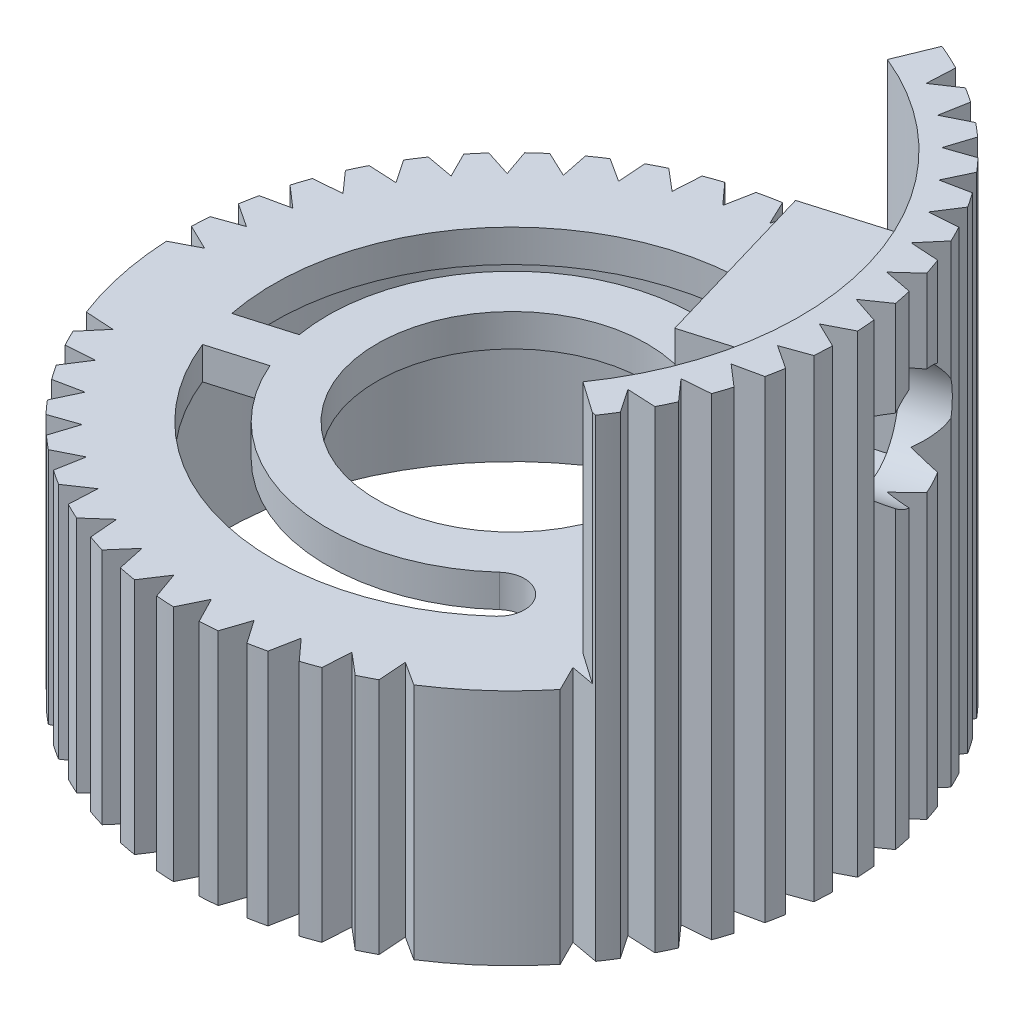
SolidWorks part; units mm, degrees
material "VeroWhite Plus"
ref_plane "Front Plane" through (0, 0, 0) normal (0, 0, 1) x (1, 0, 0)
ref_plane "Top Plane" through (0, 0, 0) normal (0, 1, 0) x (1, 0, 0)
ref_plane "Right Plane" through (0, 0, 0) normal (1, 0, 0) x (0, 0, -1)
sketch "Sketch1" plane through (0, 0, 0) normal (0, 1, 0) x (1, 0, 0)
  line L0 (9.9132, 31.394) -> (7.112, 32.1446) construction
  line L1 (11.113, 31.0725) -> (5.9121, 32.4661) construction
  line L2 (8.5126, 31.7693) -> (0, 0) construction
  line L3 (0, 0) -> (-6.2397, 29.8549) construction
  line L4 (0, 0) -> (-5.194, 30.0545) construction
  line L5 (0, 0) -> (-4.3196, 30.1926) construction
  line L6 (-4.9343, 30.0982) -> (-4.1426, 28.9552) construction
  line L7 (-4.1426, 28.9552) -> (-3.7032, 30.2744) construction
  line L8 (5.9121, 32.4661) -> (4.002, 25.3375) construction
  line L9 (11.113, 31.0725) -> (9.4356, 24.8123) construction
  line L10 (-32.4661, -5.9121) -> (-31.0725, -11.113) construction
  line L11 (-32.1446, -7.112) -> (-31.394, -9.9131) construction
  line L12 (22.2314, -24.282) -> (24.282, -22.2314) construction
  line L13 (-31.7693, -8.5126) -> (0, 0) construction
  line L14 (0, 0) -> (23.2567, -23.2567) construction
  line L15 (25.1604, -21.3531) -> (18.9649, -15.1575) construction
  line L16 (21.3531, -25.1604) -> (14.6891, -18.4964) construction
  line L17 (-32.4661, -5.9121) -> (-24.142, -3.6817) construction
  line L18 (-31.0725, -11.113) -> (-21.737, -8.6116) construction
  line L19 (-0.9635, 30.4848) -> (-0.3278, 29.2482) construction
  line L20 (-0.3278, 29.2482) -> (0.2801, 30.4987) construction
  line L21 (3.0238, 30.3497) -> (3.4927, 29.0407) construction
  line L22 (3.4927, 29.0407) -> (4.2586, 30.2012) construction
  line L23 (14.408, 26.8823) -> (14.3402, 25.4935) construction
  line L24 (14.3402, 25.4935) -> (15.4919, 26.2726) construction
  line L25 (17.7936, 24.7717) -> (17.5451, 23.4037) construction
  line L26 (17.5451, 23.4037) -> (18.7887, 24.0257) construction
  line L27 (20.8747, 22.2373) -> (20.4498, 20.9133) construction
  line L28 (20.4498, 20.9133) -> (21.7639, 21.3678) construction
  line L29 (23.5987, 19.3223) -> (23.0046, 18.0652) construction
  line L30 (23.0046, 18.0652) -> (24.3668, 18.3442) construction
  line L31 (25.9189, 16.0768) -> (25.1658, 14.9079) construction
  line L32 (25.1658, 14.9079) -> (26.5527, 15.0068) construction
  line L33 (27.7956, 12.5562) -> (26.8964, 11.4956) construction
  line L34 (26.8964, 11.4956) -> (28.2843, 11.4126) construction
  line L35 (29.1967, 8.8207) -> (28.1667, 7.8866) construction
  line L36 (28.1667, 7.8866) -> (29.532, 7.6231) construction
  line L37 (30.0982, 4.9343) -> (28.9552, 4.1426) construction
  line L38 (28.9552, 4.1426) -> (30.2744, 3.7032) construction
  line L39 (30.4848, 0.9635) -> (29.2482, 0.3278) construction
  line L40 (29.2482, 0.3278) -> (30.4987, -0.2801) construction
  line L41 (30.3497, -3.0238) -> (29.0407, -3.4927) construction
  line L42 (29.0407, -3.4927) -> (30.2012, -4.2586) construction
  line L43 (29.6954, -6.9594) -> (28.3364, -7.2534) construction
  line L44 (28.3364, -7.2534) -> (29.387, -8.1642) construction
  line L45 (28.533, -10.7759) -> (27.1472, -10.89) construction
  line L46 (27.1472, -10.89) -> (28.07, -11.9301) construction
  line L47 (26.8823, -14.408) -> (25.4935, -14.3402) construction
  line L48 (25.4935, -14.3402) -> (26.2726, -15.4919) construction
  line L49 (24.7717, -17.7936) -> (23.4037, -17.5451) construction
  line L50 (23.4037, -17.5451) -> (24.0257, -18.7887) construction
  line L51 (16.0768, -25.9188) -> (14.9079, -25.1658) construction
  line L52 (14.9079, -25.1658) -> (15.0068, -26.5527) construction
  line L53 (12.5562, -27.7955) -> (11.4956, -26.8963) construction
  line L54 (11.4956, -26.8963) -> (11.4126, -28.2843) construction
  line L55 (8.8207, -29.1967) -> (7.8866, -28.1667) construction
  line L56 (7.8866, -28.1667) -> (7.6231, -29.532) construction
  line L57 (4.9343, -30.0982) -> (4.1426, -28.9552) construction
  line L58 (4.1426, -28.9552) -> (3.7032, -30.2743) construction
  line L59 (0.9635, -30.4848) -> (0.3278, -29.2482) construction
  line L60 (0.3278, -29.2482) -> (-0.2801, -30.4987) construction
  line L61 (-3.0238, -30.3497) -> (-3.4927, -29.0407) construction
  line L62 (-3.4927, -29.0407) -> (-4.2586, -30.2012) construction
  line L63 (-6.9594, -29.6954) -> (-7.2534, -28.3364) construction
  line L64 (-7.2534, -28.3364) -> (-8.1642, -29.387) construction
  line L65 (-10.7759, -28.533) -> (-10.89, -27.1472) construction
  line L66 (-10.89, -27.1472) -> (-11.9301, -28.0699) construction
  line L67 (-14.408, -26.8823) -> (-14.3402, -25.4935) construction
  line L68 (-14.3402, -25.4935) -> (-15.4919, -26.2726) construction
  line L69 (-17.7936, -24.7717) -> (-17.5451, -23.4037) construction
  line L70 (-17.5451, -23.4037) -> (-18.7886, -24.0257) construction
  line L71 (-20.8747, -22.2373) -> (-20.4498, -20.9133) construction
  line L72 (-20.4498, -20.9133) -> (-21.7639, -21.3678) construction
  line L73 (-23.5987, -19.3223) -> (-23.0046, -18.0652) construction
  line L74 (-23.0046, -18.0652) -> (-24.3668, -18.3442) construction
  line L75 (-25.9188, -16.0768) -> (-25.1658, -14.9079) construction
  line L76 (-25.1658, -14.9079) -> (-26.5527, -15.0068) construction
  line L77 (-27.7955, -12.5562) -> (-26.8963, -11.4956) construction
  line L78 (-26.8963, -11.4956) -> (-28.2843, -11.4126) construction
  line L79 (-30.4848, -0.9635) -> (-29.2482, -0.3278) construction
  line L80 (-29.2482, -0.3278) -> (-30.4987, 0.2801) construction
  line L81 (-30.3497, 3.0238) -> (-29.0407, 3.4927) construction
  line L82 (-29.0407, 3.4927) -> (-30.2012, 4.2586) construction
  line L83 (-29.6954, 6.9594) -> (-28.3364, 7.2534) construction
  line L84 (-28.3364, 7.2534) -> (-29.387, 8.1642) construction
  line L85 (-28.533, 10.7759) -> (-27.1472, 10.89) construction
  line L86 (-27.1472, 10.89) -> (-28.0699, 11.9301) construction
  line L87 (-26.8823, 14.408) -> (-25.4935, 14.3402) construction
  line L88 (-25.4935, 14.3402) -> (-26.2726, 15.4919) construction
  line L89 (-24.7717, 17.7936) -> (-23.4037, 17.5451) construction
  line L90 (-23.4037, 17.5451) -> (-24.0257, 18.7887) construction
  line L91 (-22.2373, 20.8747) -> (-20.9133, 20.4498) construction
  line L92 (-20.9133, 20.4498) -> (-21.3678, 21.7639) construction
  line L93 (-19.3223, 23.5987) -> (-18.0652, 23.0046) construction
  line L94 (-18.0652, 23.0046) -> (-18.3442, 24.3668) construction
  line L95 (-16.0768, 25.9189) -> (-14.9079, 25.1658) construction
  line L96 (-14.9079, 25.1658) -> (-15.0068, 26.5527) construction
  line L97 (-12.5562, 27.7956) -> (-11.4956, 26.8964) construction
  line L98 (-11.4956, 26.8964) -> (-11.4126, 28.2843) construction
  line L99 (-8.8207, 29.1967) -> (-7.8866, 28.1667) construction
  line L100 (-7.8866, 28.1667) -> (-7.6231, 29.532) construction
  line L101 (-3.9843, 27.8484) -> (-3.1555, 30.3363)
  line L102 (-1.5142, 30.4624) -> (-0.3152, 28.1302)
  line L103 (-0.3152, 28.1302) -> (0.8312, 30.4887)
  line L104 (2.4749, 30.3994) -> (3.3592, 27.9307)
  line L105 (3.3592, 27.9307) -> (4.8036, 30.1194)
  line L106 (13.9199, 27.1383) -> (13.7921, 24.5191)
  line L107 (13.7921, 24.5191) -> (15.9641, 25.9884)
  line L108 (17.3431, 25.0892) -> (16.8745, 22.5091)
  line L109 (16.8745, 22.5091) -> (19.2197, 23.6823)
  line L110 (20.4695, 22.6109) -> (19.6682, 20.114)
  line L111 (19.6682, 20.114) -> (22.1465, 20.971)
  line L112 (23.2457, 19.7456) -> (22.1253, 17.3747)
  line L113 (22.1253, 17.3747) -> (24.6943, 17.9009)
  line L114 (25.6241, 16.5425) -> (24.2039, 14.3381)
  line L115 (24.2039, 14.3381) -> (26.8195, 14.5245)
  line L116 (27.5641, 13.0564) -> (25.8683, 11.0562)
  line L117 (25.8683, 11.0562) -> (28.4859, 10.8996)
  line L118 (29.0325, 9.3468) -> (27.0901, 7.5851)
  line L119 (27.0901, 7.5851) -> (29.6649, 7.0882)
  line L120 (30.0041, 5.4774) -> (27.8484, 3.9843)
  line L121 (27.8484, 3.9843) -> (30.3363, 3.1555)
  line L122 (30.4624, 1.5142) -> (28.1302, 0.3152)
  line L123 (28.1302, 0.3152) -> (30.4887, -0.8312)
  line L124 (30.3994, -2.4749) -> (27.9307, -3.3592)
  line L125 (27.9307, -3.3592) -> (30.1194, -4.8036)
  line L126 (29.8163, -6.4217) -> (27.2533, -6.9761)
  line L127 (27.2533, -6.9761) -> (29.2347, -8.6939)
  line L128 (28.723, -10.2585) -> (26.1096, -10.4737)
  line L129 (26.1096, -10.4737) -> (27.8498, -12.4354)
  line L130 (27.1383, -13.9199) -> (24.5191, -13.7921)
  line L131 (24.5191, -13.7921) -> (25.9884, -15.9641)
  line L132 (25.0892, -17.343) -> (22.5091, -16.8745)
  line L133 (22.5091, -16.8745) -> (23.6823, -19.2197)
  line L134 (16.5425, -25.6241) -> (14.3381, -24.2038)
  line L135 (14.3381, -24.2038) -> (14.5245, -26.8195)
  line L136 (13.0564, -27.5641) -> (11.0562, -25.8683)
  line L137 (11.0562, -25.8683) -> (10.8996, -28.4859)
  line L138 (9.3468, -29.0325) -> (7.5851, -27.0901)
  line L139 (7.5851, -27.0901) -> (7.0882, -29.6649)
  line L140 (5.4774, -30.0041) -> (3.9843, -27.8484)
  line L141 (3.9843, -27.8484) -> (3.1555, -30.3363)
  line L142 (1.5142, -30.4624) -> (0.3152, -28.1302)
  line L143 (0.3152, -28.1302) -> (-0.8311, -30.4887)
  line L144 (-2.4749, -30.3994) -> (-3.3592, -27.9307)
  line L145 (-3.3592, -27.9307) -> (-4.8036, -30.1193)
  line L146 (-6.4217, -29.8163) -> (-6.9761, -27.2533)
  line L147 (-6.9761, -27.2533) -> (-8.6939, -29.2347)
  line L148 (-10.2585, -28.723) -> (-10.4737, -26.1095)
  line L149 (-10.4737, -26.1095) -> (-12.4354, -27.8498)
  line L150 (-13.9199, -27.1383) -> (-13.7921, -24.5191)
  line L151 (-13.7921, -24.5191) -> (-15.9641, -25.9884)
  line L152 (-17.343, -25.0892) -> (-16.8745, -22.5091)
  line L153 (-16.8745, -22.5091) -> (-19.2197, -23.6823)
  line L154 (-20.4695, -22.6108) -> (-19.6681, -20.114)
  line L155 (-19.6681, -20.114) -> (-22.1465, -20.971)
  line L156 (-23.2457, -19.7456) -> (-22.1253, -17.3747)
  line L157 (-22.1253, -17.3747) -> (-24.6943, -17.9009)
  line L158 (-25.6241, -16.5425) -> (-24.2038, -14.3381)
  line L159 (-24.2038, -14.3381) -> (-26.8195, -14.5245)
  line L160 (-27.5641, -13.0564) -> (-25.8683, -11.0562)
  line L161 (-25.8683, -11.0562) -> (-28.4859, -10.8996)
  line L162 (-30.4624, -1.5142) -> (-28.1302, -0.3152)
  line L163 (-28.1302, -0.3152) -> (-30.4887, 0.8312)
  line L164 (-30.3994, 2.4749) -> (-27.9307, 3.3592)
  line L165 (-27.9307, 3.3592) -> (-30.1193, 4.8036)
  line L166 (-29.8163, 6.4217) -> (-27.2533, 6.9761)
  line L167 (-27.2533, 6.9761) -> (-29.2347, 8.6939)
  line L168 (-28.723, 10.2585) -> (-26.1095, 10.4737)
  line L169 (-26.1095, 10.4737) -> (-27.8498, 12.4354)
  line L170 (-27.1383, 13.9199) -> (-24.5191, 13.7921)
  line L171 (-24.5191, 13.7921) -> (-25.9884, 15.9641)
  line L172 (-25.0892, 17.343) -> (-22.5091, 16.8745)
  line L173 (-22.5091, 16.8745) -> (-23.6823, 19.2197)
  line L174 (-22.6108, 20.4695) -> (-20.114, 19.6682)
  line L175 (-20.114, 19.6682) -> (-20.971, 22.1465)
  line L176 (-19.7456, 23.2457) -> (-17.3747, 22.1253)
  line L177 (-17.3747, 22.1253) -> (-17.9009, 24.6943)
  line L178 (-16.5425, 25.6241) -> (-14.3381, 24.2039)
  line L179 (-14.3381, 24.2039) -> (-14.5245, 26.8195)
  line L180 (-13.0564, 27.5641) -> (-11.0562, 25.8683)
  line L181 (-11.0562, 25.8683) -> (-10.8996, 28.4859)
  line L182 (-9.3468, 29.0325) -> (-7.5851, 27.0901)
  line L183 (-7.5851, 27.0901) -> (-7.0882, 29.6649)
  line L184 (-5.0434, 30.0801) -> (-3.9843, 27.8484)
  arc A0 (21.3531, -25.1604) -> (25.1604, -21.3531) centre (0, 0) ccw construction
  arc A1 (-10.2585, -28.723) -> (-8.6939, -29.2347) centre (0, 0) ccw
  arc A2 (-6.4217, -29.8163) -> (-4.8036, -30.1193) centre (0, 0) ccw
  arc A3 (-13.9199, -27.1383) -> (-12.4354, -27.8498) centre (0, 0) ccw
  arc A4 (-17.343, -25.0892) -> (-15.9641, -25.9884) centre (0, 0) ccw
  arc A5 (-20.4695, -22.6108) -> (-19.2197, -23.6823) centre (0, 0) ccw
  arc A6 (-23.2457, -19.7456) -> (-22.1465, -20.971) centre (0, 0) ccw
  arc A7 (-25.6241, -16.5425) -> (-24.6943, -17.9009) centre (0, 0) ccw
  arc A8 (-27.5641, -13.0564) -> (-26.8195, -14.5245) centre (0, 0) ccw
  arc A9 (-2.4749, -30.3994) -> (-0.8311, -30.4887) centre (0, 0) ccw
  arc A10 (1.5142, -30.4624) -> (3.1555, -30.3363) centre (0, 0) ccw
  arc A11 (5.4774, -30.0041) -> (7.0882, -29.6649) centre (0, 0) ccw
  arc A12 (9.3468, -29.0325) -> (10.8996, -28.4859) centre (0, 0) ccw
  arc A13 (13.0564, -27.5641) -> (14.5245, -26.8195) centre (0, 0) ccw
  arc A14 (16.5425, -25.6241) -> (23.6823, -19.2197) centre (0, 0) ccw
  arc A15 (25.0892, -17.343) -> (25.9884, -15.9641) centre (0, 0) ccw
  arc A16 (28.723, -10.2585) -> (29.2347, -8.6939) centre (0, 0) ccw
  arc A17 (27.1383, -13.9199) -> (27.8498, -12.4354) centre (0, 0) ccw
  arc A18 (29.8163, -6.4217) -> (30.1194, -4.8036) centre (0, 0) ccw
  arc A19 (30.3994, -2.4749) -> (30.4887, -0.8312) centre (0, 0) ccw
  arc A20 (30.4624, 1.5142) -> (30.3363, 3.1555) centre (0, 0) ccw
  arc A21 (30.0041, 5.4774) -> (29.6649, 7.0882) centre (0, 0) ccw
  arc A22 (29.0325, 9.3468) -> (28.4859, 10.8996) centre (0, 0) ccw
  arc A23 (27.5641, 13.0564) -> (26.8195, 14.5245) centre (0, 0) ccw
  arc A24 (25.6241, 16.5425) -> (24.6943, 17.9009) centre (0, 0) ccw
  arc A25 (23.2457, 19.7456) -> (22.1465, 20.971) centre (0, 0) ccw
  arc A26 (20.4695, 22.6109) -> (19.2197, 23.6823) centre (0, 0) ccw
  arc A27 (13.9199, 27.1383) -> (4.8036, 30.1194) centre (0, 0) ccw
  arc A28 (17.3431, 25.0892) -> (15.9641, 25.9884) centre (0, 0) ccw
  arc A29 (2.4749, 30.3994) -> (0.8312, 30.4887) centre (0, 0) ccw
  arc A30 (-1.5142, 30.4624) -> (-3.1555, 30.3363) centre (0, 0) ccw
  arc A31 (-5.0434, 30.0801) -> (-7.0882, 29.6649) centre (0, 0) ccw
  arc A32 (-9.3468, 29.0325) -> (-10.8996, 28.4859) centre (0, 0) ccw
  arc A33 (-13.0564, 27.5641) -> (-14.5245, 26.8195) centre (0, 0) ccw
  arc A34 (-16.5425, 25.6241) -> (-17.9009, 24.6943) centre (0, 0) ccw
  arc A35 (-19.7456, 23.2457) -> (-20.971, 22.1465) centre (0, 0) ccw
  arc A36 (-22.6108, 20.4695) -> (-23.6823, 19.2197) centre (0, 0) ccw
  arc A37 (-25.0892, 17.343) -> (-25.9884, 15.9641) centre (0, 0) ccw
  arc A38 (-27.1383, 13.9199) -> (-27.8498, 12.4354) centre (0, 0) ccw
  arc A39 (-28.723, 10.2585) -> (-29.2347, 8.6939) centre (0, 0) ccw
  arc A40 (-29.8163, 6.4217) -> (-30.1193, 4.8036) centre (0, 0) ccw
  arc A41 (-30.3994, 2.4749) -> (-30.4887, 0.8312) centre (0, 0) ccw
  arc A42 (-30.4624, -1.5142) -> (-28.4859, -10.8996) centre (0, 0) ccw
  circle A43 centre (0, 0) radius 28.132 construction
  circle A44 centre (0, 0) radius 26.632
  dimension "D1" = 26.805
  dimension "D2" = 2
  dimension "D3" = 1.5
extrude "Boss-Extrude1" add sketch "Sketch1" along normal blind 45.77
ref_plane "Plane1" through (35.4959, 0, -10.4424) normal (0.9593, 0, -0.2822) x (-0.2822, 0, -0.9593)
sketch "Sketch3" plane through (35.4959, 0, -10.4424) normal (0.9593, 0, -0.2822) x (-0.2822, 0, -0.9593)
  circle A0 centre (0, 33.1475) radius 5
  circle A9 centre (0, 33.1475) radius 3.125
  circle A10 centre (0, 33.1475) radius 3.125 construction
  circle A11 centre (0, 33.1475) radius 4.65
  circle A12 centre (0, 33.1475) radius 4.65 construction
  dimension "D3" = 10
  dimension "D1" = 0
  dimension "D2" = 0
extrude "Cut-Extrude1" cut sketch "Sketch3" against normal blind 28.64
ref_plane "Plane2" through (25.5493, 0, -7.5163) normal (-0.9593, 0, 0.2822) x (0.2822, 0, 0.9593)
sketch "Sketch9" plane through (25.5493, 0, -7.5163) normal (-0.9593, 0, 0.2822) x (0.2822, 0, 0.9593)
  line L0 (8.25, 42.2725) -> (8.25, 24.0225)
  line L1 (6.75, 40.7725) -> (-6.75, 40.7725)
  line L2 (6.75, 40.7725) -> (6.75, 25.5225)
  line L3 (6.75, 25.5225) -> (-6.75, 25.5225)
  line L4 (-6.75, 40.7725) -> (-6.75, 25.5225)
  line L5 (6.75, 40.7725) -> (-6.75, 25.5225) construction
  line L6 (6.75, 25.5225) -> (-6.75, 40.7725) construction
  line L7 (8.25, 24.0225) -> (-8.25, 24.0225)
  line L8 (-8.25, 42.2725) -> (-8.25, 24.0225)
  line L9 (8.25, 42.2725) -> (-8.25, 42.2725)
  point P0 (0, 33.1475)
  dimension "D1" = 13.5
  dimension "D2" = 15.25
  dimension "D3" = 1.5
extrude "Boss-Extrude8" add sketch "Sketch9" along normal blind 10
sketch "Sketch11" plane through (0, 24.0225, 0) normal (0, -1, 0) x (1, 0, 0)
  circle A0 centre (0, 0) radius 26.632 construction
  circle A1 centre (0, 0) radius 26.632
  circle A2 centre (0, 0) radius 12.5
  dimension "D1" = 25
extrude "Boss-Extrude9" add sketch "Sketch11" along normal blind 3
sketch "Sketch12" plane through (0, 24.0225, 0) normal (0, 1, 0) x (1, 0, 0)
  line L0 (15.9558, 4.694) -> (0, 0) construction
  line L1 (0, 0) -> (10.0855, 24.6484) construction
  line L2 (10.0855, 24.6484) -> (21.8262, -15.2604) construction
  line L9 (21.8262, -15.2604) -> (0, 0) construction
  line L10 (0, 0) -> (10.0855, 24.6484)
  line L11 (10.0855, 24.6484) -> (17.3467, 42.3942)
  line L12 (0, 0) -> (21.8262, -15.2604)
  line L13 (21.8262, -15.2604) -> (37.5401, -26.2473)
  arc A0 (17.3467, 42.3942) -> (37.5401, -26.2473) centre (0, 0) ccw
extrude "Cut-Extrude2" cut sketch "Sketch12" along normal blind 57
sketch "Sketch13" plane through (0, 24.0225, 0) normal (0, 1, 0) x (1, 0, 0)
  line L0 (0, 0) -> (21.8262, -15.2604) construction
  line L1 (0, 0) -> (10.0855, 24.6484) construction
  line L2 (0, 0) -> (21.8262, -15.2604) construction
  line L3 (0, 0) -> (10.0855, 24.6484) construction
  circle A0 centre (0, 0) radius 26.632 construction
  circle A1 centre (0, 0) radius 26.632 construction
  circle A2 centre (0, 0) radius 12.5 construction
  circle A3 centre (0, 0) radius 12.5 construction
  circle A4 centre (0, 0) radius 19.565 construction
  arc A5 (3.5507, 19.2401) -> (13.1483, -14.4883) centre (0, 0) ccw construction
  arc A6 (4.0044, 21.6986) -> (14.8283, -16.3397) centre (0, 0) ccw
  arc A7 (3.097, 16.7816) -> (11.4682, -12.637) centre (0, 0) ccw
  arc A8 (3.097, 16.7816) -> (4.0044, 21.6986) centre (3.5507, 19.2401) ccw
  arc A9 (14.8283, -16.3397) -> (11.4682, -12.637) centre (13.1483, -14.4883) ccw
  point P9 (3.5507, 19.2401)
  point P11 (13.4037, -14.2524)
  point P14 (-18.818, -5.3547)
  dimension "D1" = 39.13
  dimension "D4" = 2.5
  dimension "D2" = 4
  dimension "D3" = 4
extrude "Cut-Extrude3" cut sketch "Sketch13" against normal blind 57
ref_plane "Plane5" through (-16.3713, 0, 4.8162) normal (-0.9593, 0, 0.2822) x (0.2822, 0, 0.9593)
sketch "Sketch14" plane through (-16.3713, 0, 4.8162) normal (-0.9593, 0, 0.2822) x (0.2822, 0, 0.9593)
  line L0 (-17.065, 21.0225) -> (17.065, 21.0225) construction
  line L1 (17.065, 24.0225) -> (-17.065, 24.0225) construction
  line L2 (-2, 21.0225) -> (2, 21.0225)
  line L3 (2, 24.0225) -> (-2, 24.0225)
  line L4 (0, 24.0225) -> (0, 21.0225) construction
  line L5 (-2, 24.0225) -> (-2, 21.0225)
  line L6 (2, 24.0225) -> (2, 21.0225)
  dimension "D1" = 2
extrude "Boss-Extrude11" add sketch "Sketch14" along normal up to surface and the other way up to surface up to face at (-5.9031, 22.5225, 1.6797) other way up to face at (-4.5654, 22.5225, 1.2991)
ref_plane "Plane6" through (-14.982, 0, 27.471) normal (0.4788, 0, -0.8779) x (0.4238, -0.8758, 0.2311)
sketch "Sketch15" plane through (-14.982, 0, 27.471) normal (0.4788, 0, -0.8779) x (0.4238, -0.8758, 0.2311)
  line L0 (-14.0544, -12.3137) -> (-17.9161, -5.3074) construction
  line L1 (-14.0544, -12.3137) -> (-17.9161, -5.3074) construction
  line L2 (-0.3732, 0.6771) -> (-4.9254, 8.9364) construction
  line L3 (-25.9639, -2.6594) -> (-22.6678, -8.6397) construction
  line L4 (-17.9161, 32.5057) -> (-4.9254, 8.9364)
  line L5 (-17.9161, -17.2609) -> (-14.0544, -24.2672)
  line L6 (-17.9161, -5.3074) -> (-17.9161, -17.2609)
  line L7 (-14.0544, -24.2672) -> (-14.0544, -12.3137)
  line L8 (-14.0544, 0) -> (-17.9161, 32.5057)
  line L9 (-17.9161, 32.5057) -> (-17.9161, -5.3074)
  line L10 (-14.0544, 0) -> (-14.0544, -12.3137)
sketch "Sketch16" plane through (0, 0, 0) normal (0, -1, 0) x (1, 0, 0)
  circle A0 centre (0, 0) radius 53.5321
extrude "Cut-Extrude5" cut sketch "Sketch16" against normal blind 2
